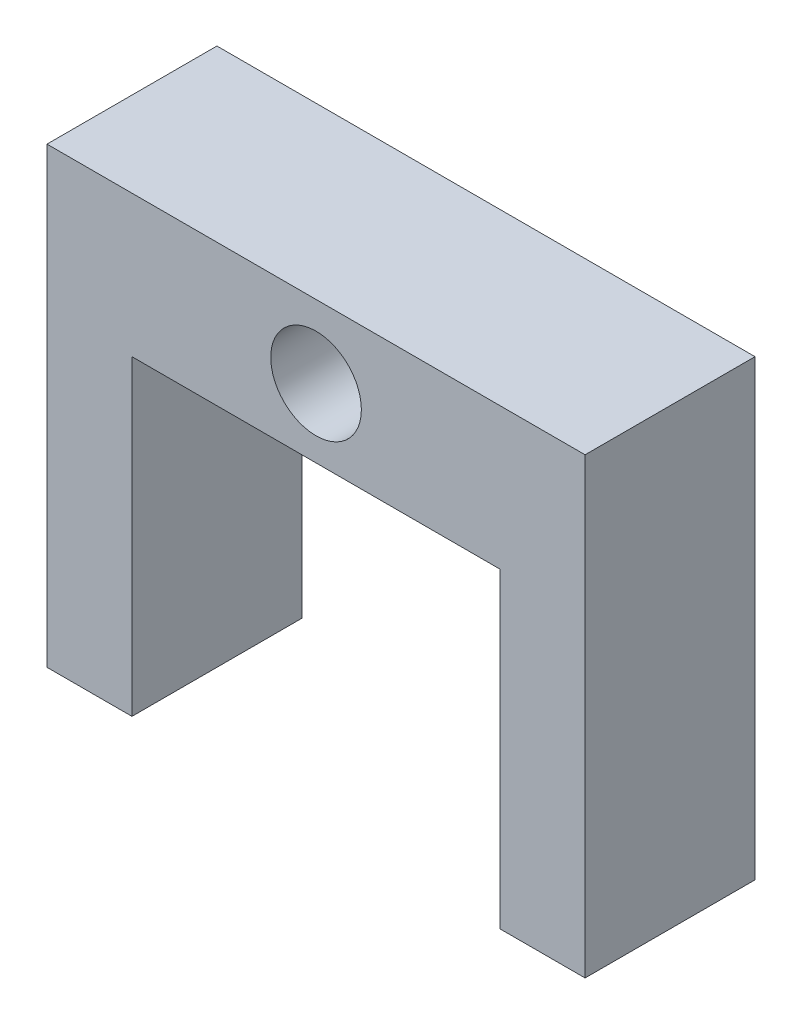
SolidWorks part; units mm, degrees
ref_plane "前视基准面" through (0, 0, 0) normal (0, 0, 1) x (1, 0, 0)
ref_plane "上视基准面" through (0, 0, 0) normal (0, 1, 0) x (1, 0, 0)
ref_plane "右视基准面" through (0, 0, 0) normal (1, 0, 0) x (0, 0, -1)
sketch "草图1" plane through (0, 0, 0) normal (0, 0, 1) x (1, 0, 0)
  line L0 (9.5, 16) -> (9.5, 0) construction
  line L1 (0, 0) -> (3, 0)
  line L2 (0, 0) -> (0, 16)
  line L3 (0, 16) -> (19, 16)
  line L4 (19, 0) -> (19, 16)
  line L6 (3, 0) -> (3, 11)
  line L7 (3, 11) -> (16, 11)
  line L8 (16, 0) -> (16, 11)
  line L9 (16, 0) -> (19, 0)
  circle A0 centre (9.5, 13.4307) radius 1.6
  dimension "D5" = 3.2
  dimension "D1" = 19
  dimension "D2" = 16
  dimension "D3" = 13
  dimension "D4" = 11
extrude "凸台-拉伸1" add sketch "草图1" along normal blind 6
